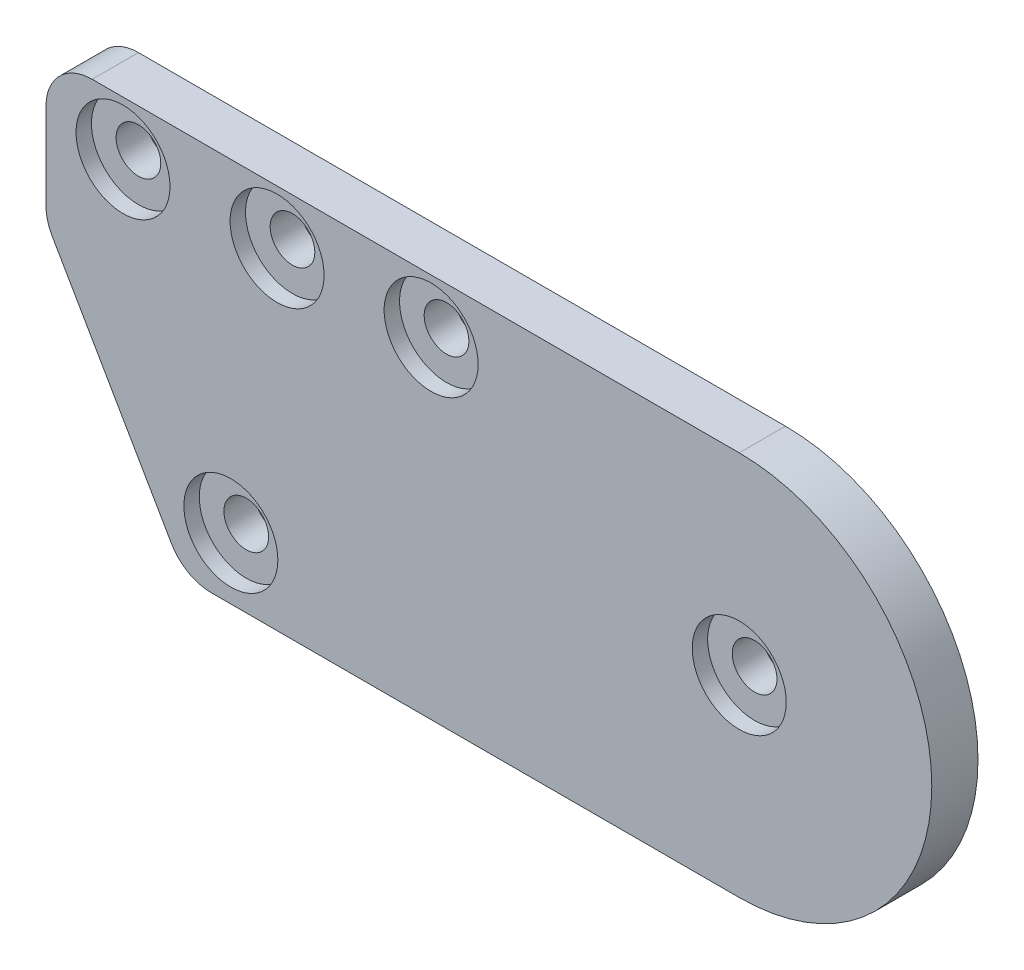
SolidWorks part; units mm, degrees
material "Thornel Mat VMA"
ref_plane "前视基准面" through (0, 0, 0) normal (0, 0, 1) x (1, 0, 0)
ref_plane "上视基准面" through (0, 0, 0) normal (0, 1, 0) x (1, 0, 0)
ref_plane "右视基准面" through (0, 0, 0) normal (1, 0, 0) x (0, 0, -1)
sketch "草图1" plane through (0, 0, 0) normal (0, 0, 1) x (1, 0, 0)
  line L0 (-20, -19) -> (20, -19)
  line L1 (-20, -20) -> (20, -20)
  line L2 (-20, -20) -> (-20, 20)
  line L3 (-20, 20) -> (20, 20)
  line L4 (20, -20) -> (20, 20)
  line L5 (-20, -20) -> (20, 20) construction
  line L6 (-20, 20) -> (20, -20) construction
  line L7 (-20, 15) -> (20, 15) construction
  line L8 (-20, 15) -> (-20, -5) construction
  line L9 (-20, -5) -> (20, -5) construction
  line L10 (20, 15) -> (20, -5) construction
  line L11 (-20, 25) -> (20, 25) construction
  line L12 (-20, 25) -> (-20, -35) construction
  line L13 (-20, -35) -> (20, -35) construction
  line L14 (20, 25) -> (20, -35) construction
  line L15 (-20, -34) -> (20, -34) construction
  line L16 (-20, -19.5) -> (20, -19.5)
  line L17 (-20, -7.89) -> (20, -7.89)
  line L18 (-20, -5.5) -> (20, -5.5)
  line L19 (-20, -33.5) -> (20, -33.5) construction
  line L20 (-20, -31.1) -> (20, -31.1) construction
  circle A0 centre (35, -19.5) radius 12.5
  point P0 (0, 0)
  dimension "D5" = 25
  dimension "D6" = 15
  dimension "D1" = 40
  dimension "D2" = 40
  dimension "D3" = 20
  dimension "D4" = 5
  dimension "D7" = 60
  dimension "D8" = 5
  dimension "D9" = 1
  dimension "D10" = 1
  dimension "D11" = 0.5
  dimension "D12" = 14
  dimension "D13" = 2.39
  dimension "D14" = 14
  dimension "D15" = 2.4
sketch "草图2" plane through (0, 0, 0) normal (0, 0, 1) x (1, 0, 0)
  line L0 (-10, -7) -> (-10, -16.4236)
  line L4 (-20, -20) -> (20, -20) construction
  line L5 (-10, -16.4236) -> (30.7247, -31.2462)
  line L6 (-10, -7) -> (35, -7)
  line L7 (-10, -10.5) -> (20, -10.5) construction
  line L8 (20, -20) -> (20, 20) construction
  line L9 (-10, -10.5) -> (20, -10.5) construction
  line L10 (-10, -16) -> (20, -16) construction
  line L11 (-20, -5.5) -> (20, -5.5) construction
  circle A0 centre (35, -19.5) radius 1.45
  circle A1 centre (35, -19.5) radius 12.5 construction
  arc A2 (35, -7) -> (30.7247, -31.2462) centre (35, -19.5) cw
  circle A3 centre (15, -10.5) radius 1.45
  circle A4 centre (5, -10.5) radius 1.45
  circle A5 centre (-5, -10.5) radius 1.45
  dimension "D3" = 5
  dimension "D7" = 20
  dimension "D8" = 15
  dimension "D9" = 10
  dimension "D11" = 45
  dimension "D12" = 2.9
  dimension "D2" = 5
  dimension "D5" = 4
  dimension "D6" = 9.5
extrude "凸台-拉伸1" add sketch "草图2" along normal blind 3
sketch "草图3" plane through (0, 0, 3) normal (0, 0, 1) x (1, 0, 0)
  line L0 (-10, -16.4236) -> (-10, -32) construction
  line L1 (-10, -32) -> (32.7959, -32) construction
  line L2 (-10, -16.4236) -> (30.7247, -31.2462) construction
  line L3 (-20, -34) -> (20, -34) construction
  line L4 (-10, -16.4236) -> (32.7959, -32)
  line L5 (-10, -28) -> (21.806, -28) construction
  line L6 (-10, -16.4236) -> (-1.0069, -32)
  line L7 (-1.0069, -32) -> (32.7959, -32)
  circle A0 centre (2, -28) radius 1.45
  dimension "D3" = 2.9
  dimension "D4" = 12
  dimension "D1" = 2
  dimension "D2" = 6
  dimension "D5" = 40
extrude "凸台-拉伸2" add sketch "草图3" against normal blind 3
sketch "草图5" plane through (0, 0, 3) normal (0, 0, 1) x (1, 0, 0)
  circle A0 centre (-5, -10.5) radius 3.05
  circle A1 centre (5, -10.5) radius 3.05
  circle A2 centre (15, -10.5) radius 3.05
  dimension "D1" = 6.1
  dimension "D2" = 6.1
  dimension "D3" = 6.1
extrude "切除-拉伸1" cut sketch "草图5" against normal blind 1
sketch "草图6" plane through (0, 0, 0) normal (0, 0, -1) x (-1, 0, 0)
  circle A0 centre (-15, -10.5) radius 3
  circle A1 centre (-5, -10.5) radius 3
  circle A2 centre (5, -10.5) radius 3
  dimension "D1" = 6
extrude "切除-拉伸2" [suppressed] cut sketch "草图6" against normal blind 1
sketch "草图7" plane through (0, 0, 3) normal (0, 0, 1) x (1, 0, 0)
  circle A0 centre (2, -28) radius 3.05
  dimension "D1" = 6.1
sketch "草图8" plane through (0, 0, 3) normal (0, 0, 1) x (1, 0, 0)
  line L0 (32.7959, -32) -> (35, -32)
  line L1 (35, -32) -> (30.7247, -31.2462)
  line L2 (30.7247, -31.2462) -> (32.7959, -32)
  arc A0 (30.7247, -31.2462) -> (35, -7) centre (35, -19.5) ccw construction
extrude "凸台-拉伸3" add sketch "草图8" against normal blind 3
extrude "切除-拉伸4" cut sketch "草图7" against normal blind 1
sketch "草图9" plane through (0, 0, 0) normal (0, 0, -1) x (-1, 0, 0)
  circle A0 centre (-2, -28) radius 3.05
  dimension "D1" = 6.1
extrude "切除-拉伸5" [suppressed] cut sketch "草图9" against normal blind 1
fillet "圆角1" radius 3 3 edges at (-10, -7, 1.5) (-10, -16.4236, 1.5) (-1.0069, -32, 1.5)
sketch "草图10" plane through (0, 0, 3) normal (0, 0, 1) x (1, 0, 0)
  circle A0 centre (35, -19.5) radius 3.05
  dimension "D1" = 6.1
extrude "切除-拉伸6" cut sketch "草图10" against normal blind 1
sketch "草图11" plane through (0, 0, 0) normal (0, 0, -1) x (-1, 0, 0)
  circle A0 centre (-35, -19.5) radius 3.05
  dimension "D1" = 6.1
extrude "切除-拉伸7" [suppressed] cut sketch "草图11" against normal blind 1
